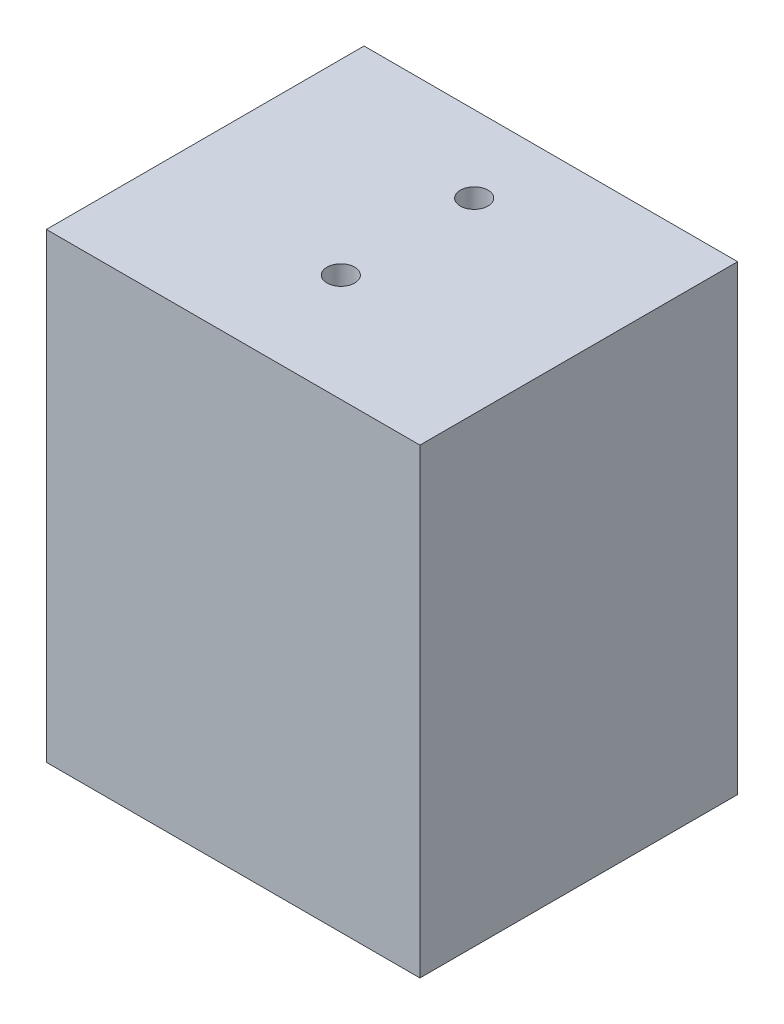
SolidWorks part; units mm, degrees
ref_plane "Front Plane" through (0, 0, 0) normal (0, 0, 1) x (1, 0, 0)
ref_plane "Top Plane" through (0, 0, 0) normal (0, 1, 0) x (1, 0, 0)
ref_plane "Right Plane" through (0, 0, 0) normal (1, 0, 0) x (0, 0, -1)
sketch "Sketch1" plane through (0, 0, 0) normal (0, 0, 1) x (1, 0, 0)
  line L1 (-47.3268, 15.1291) -> (-0.0568, 15.1291)
  line L2 (-47.3268, 15.1291) -> (-47.3268, -43.2709)
  line L3 (-47.3268, -43.2709) -> (-0.0568, -43.2709)
  line L4 (-0.0568, 15.1291) -> (-0.0568, -43.2709)
extrude "Boss-Extrude1" add sketch "Sketch1" along normal blind 40.2
sketch "Sketch4" plane through (0, -43.2709, 0) normal (0, -1, 0) x (1, 0, 0)
  line L0 (-23.6918, 0) -> (-23.6918, 40.2) construction
  line L1 (-47.3268, 0) -> (-0.0568, 0) construction
  line L2 (-47.3268, 40.2) -> (-0.0568, 40.2) construction
  circle A0 centre (-23.6918, 9.7022) radius 1.75
  circle A1 centre (-23.6918, 26.5737) radius 1.75
extrude "Cut-Extrude2" cut sketch "Sketch4" against normal blind 60
